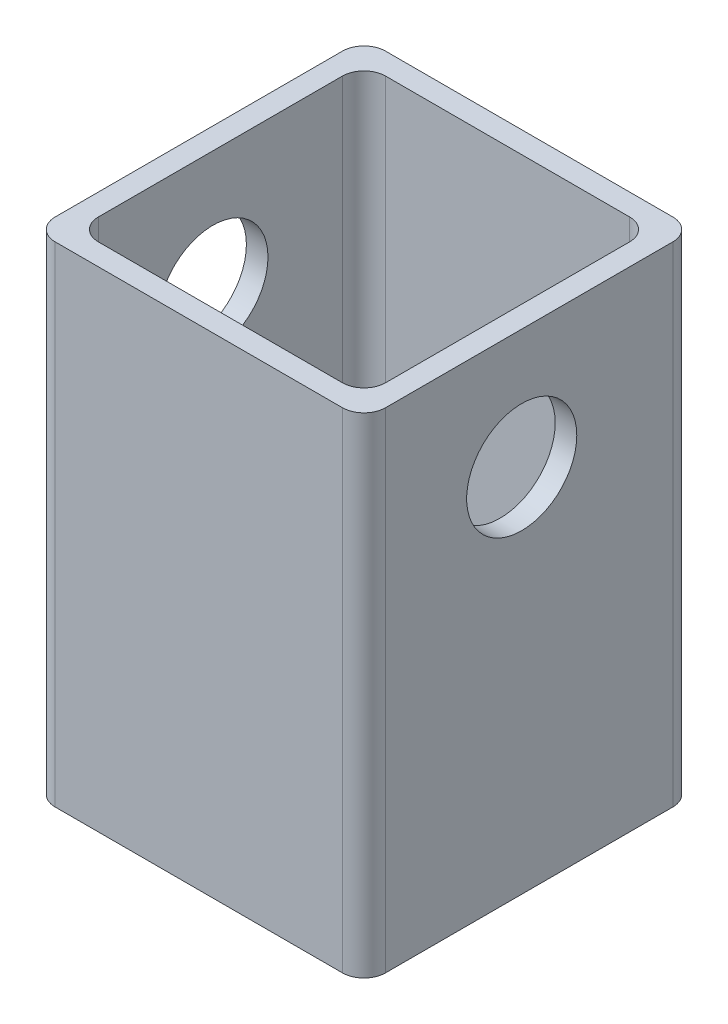
SolidWorks part; units mm, degrees
ref_plane "Front Plane" through (0, 0, 0) normal (0, 0, 1) x (1, 0, 0)
ref_plane "Top Plane" through (0, 0, 0) normal (0, 1, 0) x (1, 0, 0)
ref_plane "Right Plane" through (0, 0, 0) normal (1, 0, 0) x (0, 0, -1)
sketch "Sketch2" plane through (0, 0, 0) normal (1, 0, 0) x (0, 0, -1)
  line L0 (0, 28.2217) -> (0, 0)
other "Square tube 75X049(1)"
ref_plane "Plane2" through (0, 28.2217, 0) normal (0, -1, 0) x (0, 0, -1)
sketch "Sketch1" plane through (0, 28.2217, 0) normal (0, -1, 0) x (0, 0, -1)
  line L0 (-8.2804, 7.0358) -> (-8.2804, -7.0358)
  line L1 (-8.2804, 9.525) -> (8.2804, 9.525)
  line L2 (-9.525, 8.2804) -> (-9.525, -8.2804)
  line L3 (-8.2804, -9.525) -> (8.2804, -9.525)
  line L4 (9.525, 8.2804) -> (9.525, -8.2804)
  line L5 (-7.0358, -8.2804) -> (7.0358, -8.2804)
  line L6 (8.2804, 7.0358) -> (8.2804, -7.0358)
  line L7 (-7.0358, 8.2804) -> (7.0358, 8.2804)
  line L8 (-9.525, 9.525) -> (9.525, 9.525) construction
  line L9 (9.525, 9.525) -> (9.525, -9.525) construction
  line L10 (8.2804, 8.2804) -> (8.2804, -8.2804) construction
  line L11 (-8.2804, 8.2804) -> (8.2804, 8.2804) construction
  line L12 (-8.2804, -8.2804) -> (8.2804, -8.2804) construction
  line L13 (-9.525, -9.525) -> (9.525, -9.525) construction
  line L14 (-9.525, 9.525) -> (-9.525, -9.525) construction
  line L15 (-8.2804, 8.2804) -> (-8.2804, -8.2804) construction
  arc A0 (8.2804, 9.525) -> (9.525, 8.2804) centre (8.2804, 8.2804) cw
  arc A1 (8.2804, 7.0358) -> (7.0358, 8.2804) centre (7.0358, 7.0358) ccw
  arc A2 (7.0358, -8.2804) -> (8.2804, -7.0358) centre (7.0358, -7.0358) ccw
  arc A3 (8.2804, -9.525) -> (9.525, -8.2804) centre (8.2804, -8.2804) ccw
  arc A4 (-9.525, -8.2804) -> (-8.2804, -9.525) centre (-8.2804, -8.2804) ccw
  arc A5 (-8.2804, -7.0358) -> (-7.0358, -8.2804) centre (-7.0358, -7.0358) ccw
  arc A6 (-8.2804, 7.0358) -> (-7.0358, 8.2804) centre (-7.0358, 7.0358) cw
  arc A7 (-8.2804, 9.525) -> (-9.525, 8.2804) centre (-8.2804, 8.2804) ccw
  point P4 (-9.525, 0)
  point P6 (0, 9.525)
  point P14 (9.525, 9.525)
  point P36 (0, 0)
  dimension "D4" = 1.2446
  dimension "D3" = 1.2446
sketch "Sketch3" plane through (9.525, 0, 0) normal (1, 0, 0) x (0, 0, -1)
  circle A0 centre (-0.4315, 21.3316) radius 3.175
  dimension "D1" = 6.35
extrude "Cut-Extrude1" cut sketch "Sketch3" against normal through all
